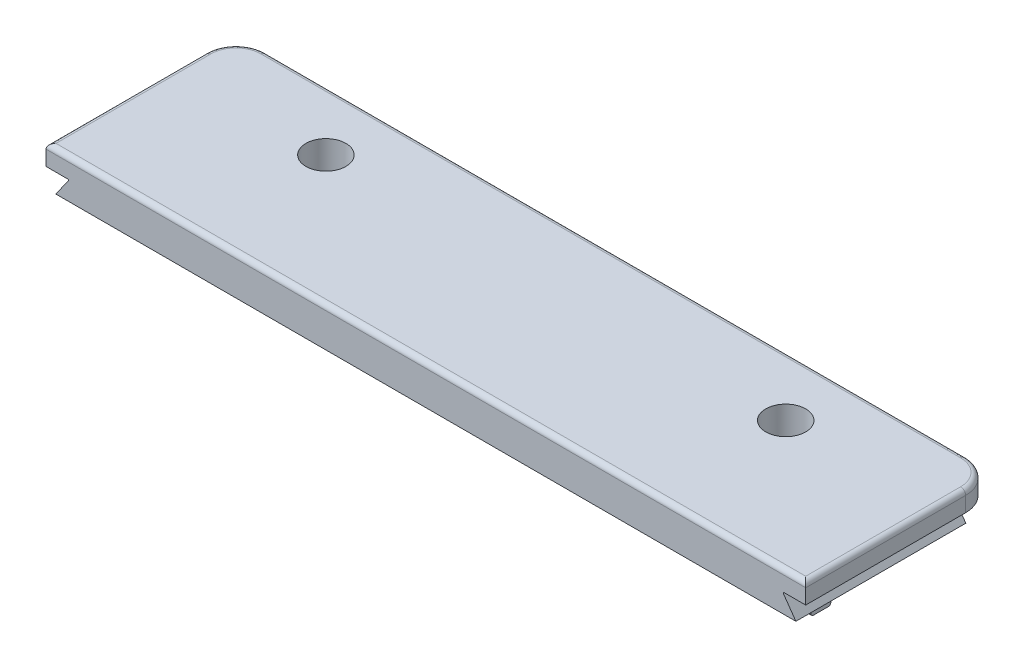
SolidWorks part; units mm, degrees
ref_plane "Front Plane" through (0, 0, 0) normal (0, 0, 1) x (1, 0, 0)
ref_plane "Top Plane" through (0, 0, 0) normal (0, 1, 0) x (1, 0, 0)
ref_plane "Right Plane" through (0, 0, 0) normal (1, 0, 0) x (0, 0, -1)
sketch "Sketch1" plane through (0, 0, 0) normal (0, 0, 1) x (1, 0, 0)
  line L0 (-14.5, 22) -> (-30.9004, 22) construction
  line L1 (37.4004, 22) -> (-37.4004, 22) construction
  line L4 (36, 24) -> (37.4004, 22) construction
  line L6 (-37.4004, 22) -> (-36, 24) construction
  line L7 (35.7558, 24) -> (37.0162, 22.2)
  line L8 (37.0162, 22.2) -> (-37.0162, 22.2)
  line L9 (-37.0162, 22.2) -> (-35.7558, 24)
  line L10 (33.8176, 26.768) -> (37.0162, 22.2) construction
  line L11 (-29.5, 24) -> (29.5, 24) construction
  line L12 (-37.0162, 22.2) -> (-33.8643, 26.7014) construction
  line L13 (-35.7558, 24) -> (-35.7558, 24.1)
  line L14 (-35.7558, 24.1) -> (-38, 24.1)
  line L15 (-38, 24.1) -> (-38, 26.1)
  line L16 (-38, 26.1) -> (38, 26.1)
  line L18 (0, 2) -> (0, 26.1) construction
  line L19 (29.5, 2) -> (-29.5, 2) construction
  line L20 (35.7558, 24) -> (35.7558, 24.1)
  line L21 (35.7558, 24.1) -> (38, 24.1)
  line L22 (38, 24.1) -> (38, 26.1)
  line L23 (33.9815, 26.8828) -> (37.4004, 22) construction
  line L25 (36, 24) -> (-36, 24) construction
  line L26 (-14.5, 22) -> (-37.4004, 22) construction
  line L27 (-37.4004, 22) -> (-34.0282, 26.8161) construction
  line L28 (-38, 24) -> (-36, 24) construction
  line L29 (-38, 24) -> (-38, 0.5) construction
  dimension "D2" = 0.1
  dimension "D3" = 2
  dimension "D1" = 0.2
extrude "Boss-Extrude1" add sketch "Sketch1" against normal up to surface (17 mm away) contours L16 L22 L21 L20 L7 L8 L9 L13 L14 L15
sketch "Sketch2" plane through (0, 0, -17) normal (0, 0, -1) x (-1, 0, 0)
  line L1 (-38, 24.1) -> (38, 24.1)
  line L2 (-38, 24.1) -> (-38, 26.1)
  line L3 (-38, 26.1) -> (38, 26.1)
  line L4 (38, 24.1) -> (38, 26.1)
extrude "Boss-Extrude2" add sketch "Sketch2" along normal up to surface (2 mm away)
fillet "Fillet1" radius 3 2 edges at (-38, 25.1, -19) (38, 25.1, -19)
fillet "Fillet2" radius 0.5 6 edges at (37.1213, 26.1, -18.1213) (38, 26.1, -8) (0, 26.1, 0) (-38, 26.1, -8) (-37.1213, 26.1, -18.1213) (0, 26.1, -19)
sketch "Sketch3" plane through (0, 26.1, 0) normal (0, 1, 0) x (1, 0, 0)
  line L0 (0, 0) -> (0, 19) construction
  line L1 (-35, 19) -> (35, 19) construction
  line L2 (38, 13) -> (-38, 13) construction
  line L3 (-38, 0) -> (-38, 16) construction
  line L4 (38, 16) -> (38, 0) construction
  line L5 (-23, 11) -> (23, 11) construction
  line L6 (37.0162, 17) -> (-37.0162, 17) construction
  circle A0 centre (-23, 13) radius 2
  circle A1 centre (23, 13) radius 2
  point P9 (0, 9.5)
  dimension "D1" = 4
  dimension "D2" = 15
  dimension "D3" = 6
extrude "Cut-Extrude1" cut sketch "Sketch3" against normal up to next
sketch "Sketch4" plane through (0, 22.2, 0) normal (0, -1, 0) x (1, 0, 0)
  line L0 (37.0162, -17) -> (37.0162, 0) construction
  line L1 (37.0162, -1.5) -> (-37.0162, -1.5)
  line L2 (37.0162, -1.5) -> (37.0162, -3.5)
  line L3 (37.0162, -3.5) -> (-37.0162, -3.5)
  line L4 (-37.0162, -1.5) -> (-37.0162, -3.5)
  line L5 (30.9004, -1.5) -> (14.5, -1.5) construction
  line L6 (-37.0162, -17) -> (-37.0162, 0) construction
  dimension "D1" = 2
extrude "Boss-Extrude3" add sketch "Sketch4" along normal blind 0.35
fillet "Fillet3" radius 0.25 2 edges at (0, 21.85, -3.5) (0, 21.85, -1.5)
